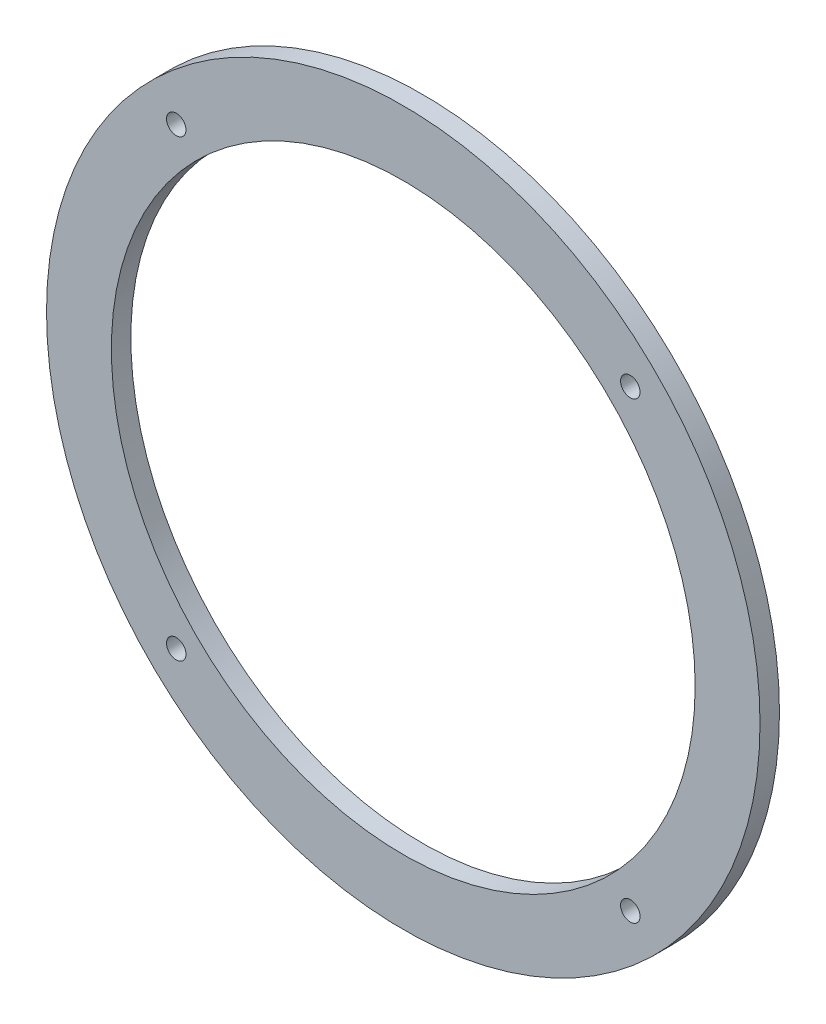
SolidWorks part; units mm, degrees
ref_plane "前视基准面" through (0, 0, 0) normal (0, 0, 1) x (1, 0, 0)
ref_plane "上视基准面" through (0, 0, 0) normal (0, 1, 0) x (1, 0, 0)
ref_plane "右视基准面" through (0, 0, 0) normal (1, 0, 0) x (0, 0, -1)
sketch "草图1" plane through (0, 0, 0) normal (0, 0, 1) x (1, 0, 0)
  line L7 (-35, -35) -> (35, -35)
  line L8 (-35, -35) -> (-35, 35)
  line L9 (-35, 35) -> (35, 35)
  line L10 (35, -35) -> (35, 35)
  line L11 (-35, -35) -> (35, 35) construction
  line L12 (-35, 35) -> (35, -35) construction
  circle A0 centre (0, 0) radius 55
  circle A1 centre (0, 0) radius 45
  circle A2 centre (-35, 35) radius 1.5
  circle A3 centre (35, 35) radius 1.5
  circle A4 centre (35, -35) radius 1.5
  circle A5 centre (-35, -35) radius 1.5
  dimension "D2" = 90
  dimension "D5" = 3
  dimension "D6" = 3
  dimension "D7" = 3
  dimension "D8" = 3
  dimension "D1" = 110
  dimension "D3" = 70
  dimension "D4" = 70
extrude "凸台-拉伸1" add sketch "草图1" along normal blind 3
